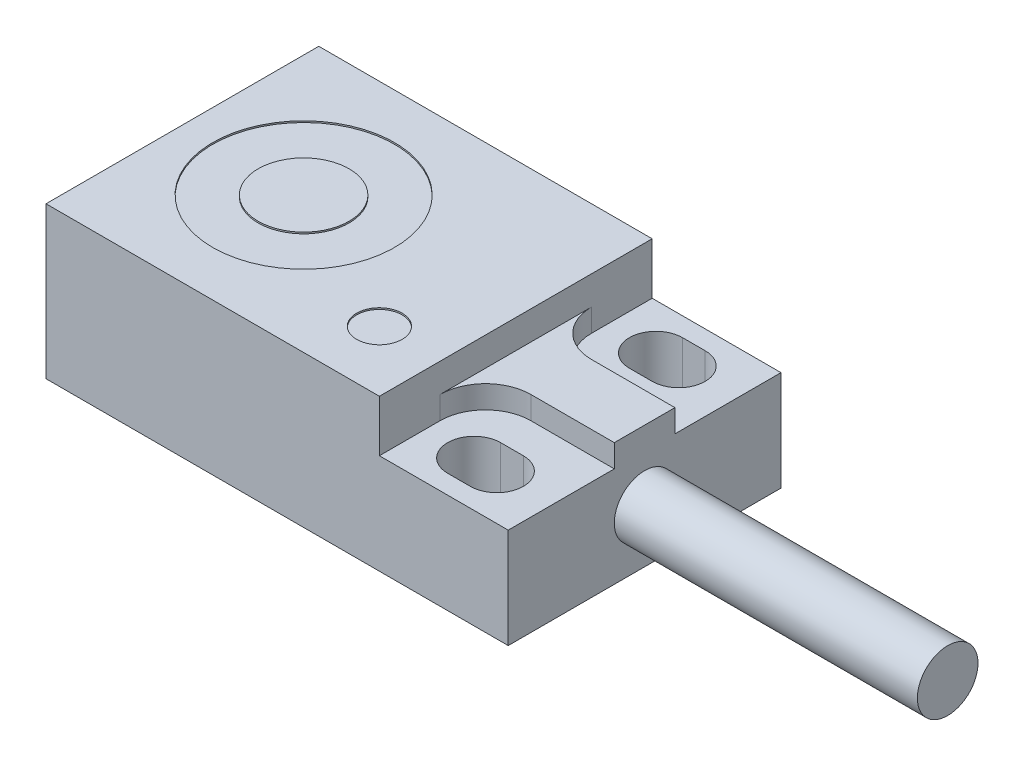
SolidWorks part; units mm, degrees
ref_plane "Plan de face" through (0, 0, 0) normal (0, 0, 1) x (1, 0, 0)
ref_plane "Plan de dessus" through (0, 0, 0) normal (0, 1, 0) x (1, 0, 0)
ref_plane "Plan de droite" through (0, 0, 0) normal (1, 0, 0) x (0, 0, -1)
sketch "Esquisse2" plane through (0, 0, 0) normal (0, 1, 0) x (1, 0, 0)
  line L1 (-15.25, 9) -> (15.25, 9)
  line L2 (-15.25, 9) -> (-15.25, -9)
  line L3 (-15.25, -9) -> (15.25, -9)
  line L4 (15.25, 9) -> (15.25, -9)
  point P4 (0, 9)
  point P6 (-15.25, 0)
  dimension "D1" = 18
  dimension "D2" = 30.5
extrude "Boss.-Extru.1" add sketch "Esquisse2" along normal blind 10
sketch "Esquisse3" plane through (0, 10, 0) normal (0, 1, 0) x (1, 0, 0)
  line L0 (6.75, -9) -> (6.75, -2)
  line L1 (-15.25, -9) -> (15.25, -9) construction
  line L2 (6.75, -2) -> (15.25, -2)
  line L3 (15.25, -9) -> (15.25, 9) construction
  line L4 (0, 0) -> (4.6005, 0) construction
  line L5 (6.75, -9) -> (15.25, -9)
  line L6 (15.25, -9) -> (15.25, -2)
  line L7 (15.25, 9) -> (15.25, 2)
  line L8 (6.75, 9) -> (15.25, 9)
  line L9 (6.75, 2) -> (15.25, 2)
  line L10 (6.75, 9) -> (6.75, 2)
  dimension "D1" = 4
  dimension "D2" = 8.5
extrude "Enlèv. mat.-Extru.1" cut sketch "Esquisse3" against normal blind 3.4
sketch "Esquisse4" plane through (0, 6.6, 0) normal (0, 1, 0) x (1, 0, 0)
  line L0 (10, 6) -> (11.5, 6) construction
  line L4 (15.25, 2) -> (15.25, 9) construction
  line L5 (10, 7.75) -> (11.5, 7.75)
  line L6 (10, 4.25) -> (11.5, 4.25)
  line L7 (0, 0) -> (3.2346, 0) construction
  line L8 (10, -6) -> (11.5, -6) construction
  line L9 (10, -7.75) -> (11.5, -7.75)
  line L10 (10, -4.25) -> (11.5, -4.25)
  arc A2 (10, 7.75) -> (10, 4.25) centre (10, 6) ccw
  arc A3 (11.5, 4.25) -> (11.5, 7.75) centre (11.5, 6) ccw
  arc A4 (10, -7.75) -> (10, -4.25) centre (10, -6) cw
  arc A5 (11.5, -4.25) -> (11.5, -7.75) centre (11.5, -6) cw
  point P2 (10.75, 6)
  point P7 (13.25, 6)
  point P9 (8.25, 6)
  point P20 (10.75, -6)
  dimension "D1" = 5
  dimension "D2" = 3.5
  dimension "D3" = 4.5
  dimension "D4" = 12
extrude "Enlèv. mat.-Extru.2" cut sketch "Esquisse4" against normal through all
sketch "Esquisse7" plane through (0, 10, 0) normal (0, 1, 0) x (1, 0, 0)
  line L1 (15.25, 2) -> (6.75, 2)
  line L2 (15.25, 2) -> (15.25, -2)
  line L3 (15.25, -2) -> (6.75, -2)
  line L4 (6.75, 2) -> (6.75, -2)
extrude "Enlèv. mat.-Extru.4" cut sketch "Esquisse7" against normal blind 1.9
fillet "Congé1" radius 3 2 edges at (6.75, 7.35, -2) (6.75, 7.35, 2)
sketch "Esquisse5" plane through (0, 10, 0) normal (0, 1, 0) x (1, 0, 0)
  line L0 (11.5, 7.75) -> (10, 7.75) construction
  line L1 (-15.25, -9) -> (6.75, -9) construction
  line L2 (6.75, 9) -> (6.75, -9) construction
  circle A0 centre (-7.25, 0) radius 6
  circle A1 centre (-7.25, 0) radius 3
  circle A2 centre (2.75, -5) radius 1.5
  point P6 (10.75, 7.75)
  dimension "D2" = 12
  dimension "D3" = 6
  dimension "D4" = 3
  dimension "D1" = 18
  dimension "D5" = 4
  dimension "D6" = 4
extrude "Enlèv. mat.-Extru.3" cut sketch "Esquisse5" against normal blind 0.1
sketch "Esquisse6" plane through (15.25, 0, 0) normal (1, 0, 0) x (0, 0, -1)
  line L0 (-9, 0) -> (9, 0) construction
  circle A0 centre (0, 3.5) radius 2
  point P5 (0, 0)
  dimension "D1" = 4
  dimension "D2" = 3.5
extrude "Boss.-Extru.2" add sketch "Esquisse6" along normal blind 20
ref_plane "Plan1" through (10.75, 0, 0) normal (1, 0, 0) x (0, 0, -1)
